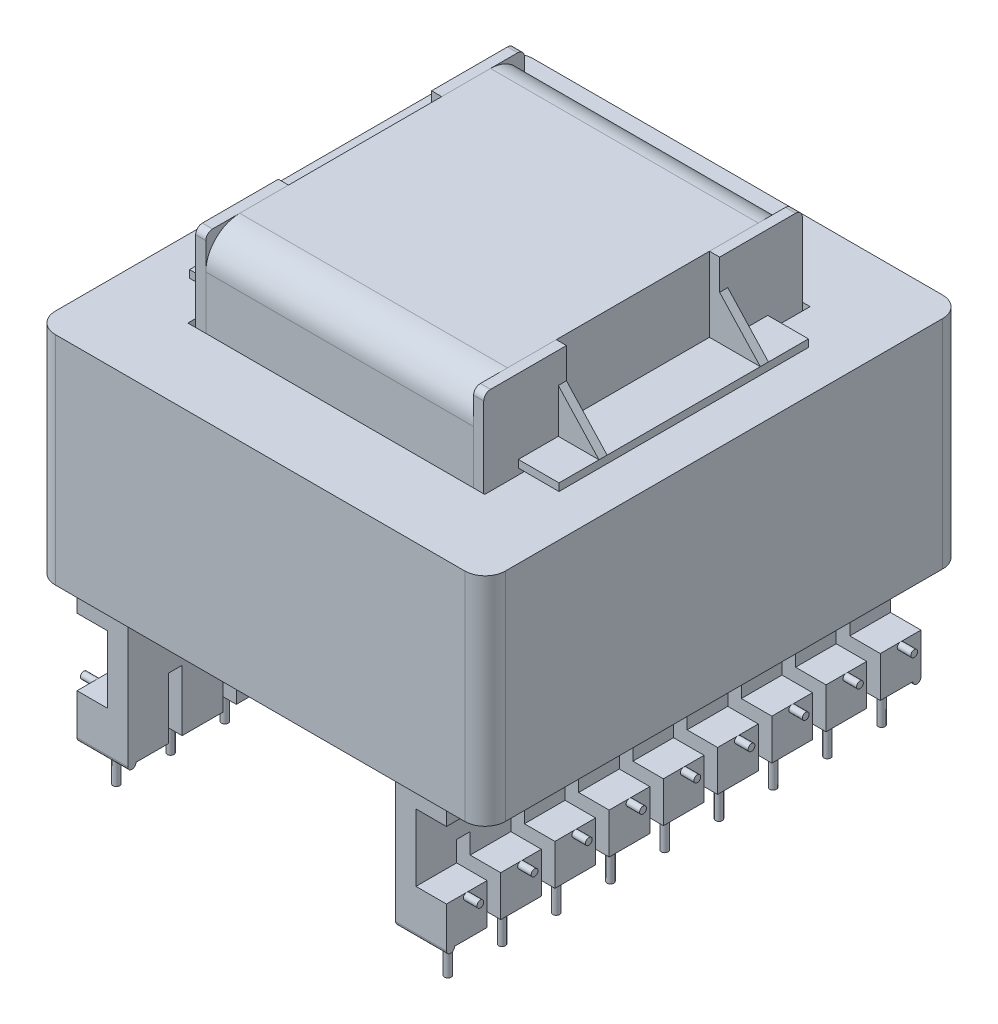
SolidWorks part; units mm, degrees
ref_plane "Спереди" through (0, 0, 0) normal (0, 0, 1) x (1, 0, 0)
ref_plane "Сверху" through (0, 0, 0) normal (0, 1, 0) x (1, 0, 0)
ref_plane "Справа" through (0, 0, 0) normal (1, 0, 0) x (0, 0, -1)
sketch "Эскиз1" plane through (0, 0, 0) normal (1, 0, 0) x (0, 0, -1)
  line L1 (-11.3, 16.25) -> (11.3, 16.25)
  line L2 (-11.3, 16.25) -> (-11.3, -16.25)
  line L3 (-11.3, -16.25) -> (11.3, -16.25)
  line L4 (11.3, 16.25) -> (11.3, -16.25)
  line L5 (-11.3, 16.25) -> (11.3, -16.25) construction
  line L6 (-11.3, -16.25) -> (11.3, 16.25) construction
  line L7 (-12.5, 17.35) -> (12.5, 17.35)
  line L8 (-12.5, 17.35) -> (-12.5, -17.35)
  line L9 (-12.5, -17.35) -> (12.5, -17.35)
  line L10 (12.5, 17.35) -> (12.5, -17.35)
  line L11 (-12.5, 17.35) -> (12.5, -17.35) construction
  line L12 (-12.5, -17.35) -> (12.5, 17.35) construction
  point P0 (0, 0)
  point P6 (0, 0)
  dimension "D1" = 22.6
  dimension "D2" = 32.5
  dimension "D3" = 25
  dimension "D4" = 34.7
extrude "Бобышка-Вытянуть1" add sketch "Эскиз1" along normal blind 19.75
sketch "Эскиз2" plane through (19.75, 0, 0) normal (1, 0, 0) x (0, 0, -1)
  line L0 (-12.5, -17.35) -> (12.5, -17.35) construction
  line L1 (11.3, -17.35) -> (23.5, -17.35)
  line L2 (11.3, -17.35) -> (11.3, 28.35)
  line L3 (11.3, 28.35) -> (22.5, 28.35)
  line L4 (23.5, -17.35) -> (23.5, 27.35)
  line L5 (11.3, 16.25) -> (-11.3, 16.25) construction
  line L6 (11.3, -16.25) -> (11.3, 16.25) construction
  line L7 (0, 0) -> (0, 38.0092) construction
  line L8 (-23.5, -17.35) -> (-23.5, 27.35)
  line L9 (-11.3, 28.35) -> (-22.5, 28.35)
  line L10 (-11.3, -17.35) -> (-11.3, 28.35)
  line L11 (-11.3, -17.35) -> (-23.5, -17.35)
  arc A0 (22.5, 28.35) -> (23.5, 27.35) centre (22.5, 27.35) cw
  arc A1 (-22.5, 28.35) -> (-23.5, 27.35) centre (-22.5, 27.35) ccw
  dimension "D3" = 1
  dimension "D1" = 23.5
  dimension "D2" = 12.1
extrude "Бобышка-Вытянуть2" add sketch "Эскиз2" along normal blind 1.5
sketch "Эскиз3" plane through (19.75, 0, 0) normal (1, 0, 0) x (0, 0, -1)
  line L0 (11.3, 16.25) -> (-11.3, 16.25) construction
  line L1 (18.4, 16.25) -> (-18.4, 16.25)
  line L2 (0, 16.25) -> (0, 17.35)
  line L3 (18.4, 17.35) -> (-18.4, 17.35)
  line L4 (-18.4, 16.25) -> (-18.4, 17.35)
  line L5 (11.3, 17.35) -> (-11.3, 17.35) construction
  line L6 (18.4, 16.25) -> (18.4, 17.35)
  line L7 (-11.3, -17.35) -> (11.3, -17.35) construction
  line L8 (-35, -17.35) -> (35, -17.35)
  line L9 (0, -17.35) -> (0, -16.25)
  line L10 (-35, -16.25) -> (35, -16.25)
  line L11 (35, -17.35) -> (35, -16.25)
  line L12 (-11.3, -16.25) -> (11.3, -16.25) construction
  line L13 (-35, -17.35) -> (-35, -16.25)
  dimension "D1" = 18.4
  dimension "D2" = 35
extrude "Бобышка-Вытянуть3" add sketch "Эскиз3" along normal blind 7.5 contours L1 L4 L3 L6 | L10 L11 L8 L13
sketch "Эскиз4" plane through (0, 17.35, 0) normal (0, 1, 0) x (1, 0, 0)
  line L0 (27.25, 18.4) -> (27.25, -18.4) construction
  line L1 (21.25, -11.3) -> (27.25, -11.3)
  line L2 (21.25, -11.3) -> (21.25, -12.5)
  line L3 (21.25, -12.5) -> (27.25, -12.5)
  line L4 (27.25, -11.3) -> (27.25, -12.5)
  line L5 (19.75, 12.5) -> (0, 12.5) construction
  line L6 (21.25, 11.3) -> (27.25, 11.3)
  line L7 (21.25, 11.3) -> (21.25, 12.5)
  line L8 (21.25, 12.5) -> (27.25, 12.5)
  line L9 (27.25, 11.3) -> (27.25, 12.5)
  line L10 (19.75, -12.5) -> (0, -12.5) construction
  point P16 (0, 0)
  point P17 (0, 0)
  point P18 (0, 0)
extrude "Бобышка-Вытянуть4" add sketch "Эскиз4" along normal blind 6.5 contours L8 L9 L6 L7 | L1 L4 L3 L2
sketch "Эскиз5" plane through (0, 0, -12.5) normal (0, 0, -1) x (-1, 0, 0)
  line L0 (-21.25, 23.85) -> (-27.25, 17.35)
  line L1 (-27.25, 17.35) -> (-27.25, 23.85)
  line L2 (-27.25, 23.85) -> (-21.25, 23.85)
  line L3 (-21.25, 23.85) -> (-21.2719, 23.84)
extrude "Вырез-Вытянуть1" cut sketch "Эскиз5" against normal through all
sketch "Эскиз6" plane through (0, -17.35, 0) normal (0, -1, 0) x (-1, 0, 0)
  line L1 (-27.25, -35) -> (-19.75, -35)
  line L2 (-27.25, -35) -> (-27.25, 35)
  line L3 (-27.25, 35) -> (-19.75, 35)
  line L4 (-19.75, -35) -> (-19.75, 35)
extrude "Бобышка-Вытянуть5" add sketch "Эскиз6" along normal offset from surface (16.8 mm away) 62.5 up to face at (20.5, 28.35, -16.9)
sketch "Эскиз7" plane through (0, 0, -35) normal (0, 0, -1) x (-1, 0, 0)
  line L0 (-27.25, -34.15) -> (-27.25, -16.25) construction
  line L1 (-27.25, -28.15) -> (-22.75, -28.15)
  line L2 (-27.25, -28.15) -> (-27.25, -18.25)
  line L3 (-27.25, -18.25) -> (-22.75, -18.25)
  line L4 (-22.75, -28.15) -> (-22.75, -18.25)
  line L5 (-19.75, -34.15) -> (-19.75, -16.25) construction
  line L6 (-27.25, -16.25) -> (-19.75, -16.25) construction
  line L7 (-19.75, -34.15) -> (-27.25, -34.15) construction
  dimension "D1" = 3
  dimension "D2" = 2
  dimension "D3" = 6
extrude "Вырез-Вытянуть2" cut sketch "Эскиз7" against normal up to next
sketch "Эскиз9" plane through (0, -34.15, 0) normal (0, -1, 0) x (1, 0, 0)
  line L0 (0, 12.5) -> (0, -12.5) construction
  circle A0 centre (24.45, 32) radius 0.5
  circle A1 centre (24.45, 24) radius 0.5
  circle A2 centre (24.45, 16) radius 0.5
  circle A3 centre (24.45, 8) radius 0.5
  circle A4 centre (24.45, 0) radius 0.5
  circle A5 centre (24.45, -8) radius 0.5
  circle A6 centre (24.45, -16) radius 0.5
  circle A7 centre (24.45, -24) radius 0.5
  circle A8 centre (24.45, -32) radius 0.5
  dimension "D3" = 1
  dimension "D1" = 24.45
  dimension "D2" = 32
  dimension "D4" = 9
extrude "Бобышка-Вытянуть6" add sketch "Эскиз9" along normal blind 6
sketch "Эскиз10" plane through (27.25, 0, 0) normal (1, 0, 0) x (0, 0, -1)
  line L0 (35, -34.15) -> (-35, -34.15) construction
  line L1 (-29, -34.15) -> (-27, -34.15)
  line L2 (-29, -34.15) -> (-29, -25.15)
  line L3 (-29, -25.15) -> (-27, -25.15)
  line L4 (-27, -34.15) -> (-27, -25.15)
  line L5 (-35, -28.15) -> (35, -28.15) construction
  line L6 (-35, -34.15) -> (-35, -28.15) construction
  line L7 (-21, -34.15) -> (-19, -34.15)
  line L8 (-21, -34.15) -> (-21, -25.15)
  line L9 (-21, -25.15) -> (-19, -25.15)
  line L10 (-19, -34.15) -> (-19, -25.15)
  line L11 (-13, -34.15) -> (-11, -34.15)
  line L12 (-13, -34.15) -> (-13, -25.15)
  line L13 (-13, -25.15) -> (-11, -25.15)
  line L14 (-11, -34.15) -> (-11, -25.15)
  line L15 (-5, -34.15) -> (-3, -34.15)
  line L16 (-5, -34.15) -> (-5, -25.15)
  line L17 (-5, -25.15) -> (-3, -25.15)
  line L18 (-3, -34.15) -> (-3, -25.15)
  line L19 (3, -34.15) -> (5, -34.15)
  line L20 (3, -34.15) -> (3, -25.15)
  line L21 (3, -25.15) -> (5, -25.15)
  line L22 (5, -34.15) -> (5, -25.15)
  line L23 (11, -34.15) -> (13, -34.15)
  line L24 (11, -34.15) -> (11, -25.15)
  line L25 (11, -25.15) -> (13, -25.15)
  line L26 (13, -34.15) -> (13, -25.15)
  line L27 (19, -34.15) -> (21, -34.15)
  line L28 (19, -34.15) -> (19, -25.15)
  line L29 (19, -25.15) -> (21, -25.15)
  line L30 (21, -34.15) -> (21, -25.15)
  line L31 (27, -34.15) -> (29, -34.15)
  line L32 (27, -34.15) -> (27, -25.15)
  line L33 (27, -25.15) -> (29, -25.15)
  line L34 (29, -34.15) -> (29, -25.15)
  dimension "D1" = 3
  dimension "D2" = 6
  dimension "D3" = 2
  dimension "D4" = 8
extrude "Вырез-Вытянуть3" cut sketch "Эскиз10" against normal up to next
sketch "Эскиз11" plane through (27.25, 0, 0) normal (1, 0, 0) x (0, 0, -1)
  line L0 (-35, -28.15) -> (-29, -28.15) construction
  circle A0 centre (-32, -28.65) radius 0.5
  circle A1 centre (-24, -28.65) radius 0.5
  circle A2 centre (-16, -28.65) radius 0.5
  circle A3 centre (-8, -28.65) radius 0.5
  circle A4 centre (0, -28.65) radius 0.5
  circle A5 centre (8, -28.65) radius 0.5
  circle A6 centre (16, -28.65) radius 0.5
  circle A7 centre (24, -28.65) radius 0.5
  circle A8 centre (32, -28.65) radius 0.5
  point P2 (-32, -28.15)
  point P9 (-24, -28.15)
  point P13 (-16, -28.15)
  point P16 (-8, -28.15)
  point P19 (0, -28.15)
  point P22 (8, -28.15)
  point P25 (16, -28.15)
  point P28 (24, -28.15)
  point P31 (32, -28.15)
  dimension "D1" = 1
  dimension "D2" = 9
extrude "Бобышка-Вытянуть7" add sketch "Эскиз11" along normal blind 2
sketch "Эскиз13" plane through (27.25, 0, 0) normal (1, 0, 0) x (0, 0, -1)
  line L0 (-29, -34.15) -> (-35, -34.15) construction
  line L1 (-35, -34.15) -> (-33.8, -34.15)
  line L2 (0, -49.1553) -> (0, -4.971) construction
  line L3 (35, -34.15) -> (33.8, -34.15)
  arc A0 (-35, -34.15) -> (-33.8, -34.15) centre (-34.4, -34.15) ccw
  arc A1 (35, -34.15) -> (33.8, -34.15) centre (34.4, -34.15) cw
  dimension "D1" = 0.6
  dimension "D2" = 1.2
extrude "Бобышка-Вытянуть9" add sketch "Эскиз13" against normal up to surface (7.5 mm away) contours A1 L3 | A0 L1 up to face at (19.75, -17.5777, 0)
mirror "Зеркальное отражение1" of "Бобышка-Вытянуть9", "Бобышка-Вытянуть7", "Вырез-Вытянуть3", "Бобышка-Вытянуть6", "Вырез-Вытянуть2", "Бобышка-Вытянуть5", "Вырез-Вытянуть1", "Бобышка-Вытянуть3", "Бобышка-Вытянуть2", "Бобышка-Вытянуть1", "Бобышка-Вытянуть4"
sketch "Эскиз12" plane through (0, 0, -18.4) normal (0, 0, -1) x (-1, 0, 0)
  line L0 (21.25, 17.35) -> (27.25, 17.35)
  line L1 (27.25, 17.35) -> (21.25, 23.85)
  line L2 (21.25, 23.85) -> (21.25, 17.35)
  point P5 (0, 0)
  point P6 (21.25, 24.797)
  point P7 (21.25, 23.85)
extrude "Бобышка-Вытянуть8" add sketch "Эскиз12" against normal blind 1.5
sketch "Эскиз14" plane through (0, 0, 0) normal (1, 0, 0) x (0, 0, -1)
  line L0 (0, 0) -> (0, -16.25) construction
  line L1 (35.25, 16) -> (24, 16)
  line L2 (35.25, 16) -> (35.25, -16)
  line L3 (35.25, -16) -> (24, -16)
  line L4 (24, 16) -> (24, -16)
  line L5 (35.25, 16) -> (24, -16) construction
  line L6 (35.25, -16) -> (24, 16) construction
  line L7 (-35, -16.25) -> (35, -16.25) construction
  line L8 (-35.25, -16) -> (-24, 16) construction
  line L9 (-35.25, 16) -> (-24, -16) construction
  line L10 (-24, 16) -> (-24, -16)
  line L11 (-35.25, -16) -> (-24, -16)
  line L12 (-35.25, 16) -> (-35.25, -16)
  line L13 (-35.25, 16) -> (-24, 16)
  point P0 (29.625, 0)
  point P15 (-29.625, 0)
  dimension "D1" = 35.25
  dimension "D2" = 32
  dimension "D3" = 11.25
extrude "Бобышка-Вытянуть10" add sketch "Эскиз14" along normal blind 33.2 separate body
sketch "Эскиз15" plane through (33.2, 0, 0) normal (1, 0, 0) x (0, 0, -1)
  line L1 (24, -16) -> (-24, -16)
  line L2 (24, -16) -> (24, 16)
  line L3 (24, 16) -> (-24, 16)
  line L4 (-24, -16) -> (-24, 16)
  line L5 (24, -16) -> (-24, 16) construction
  line L6 (24, 16) -> (-24, -16) construction
  point P0 (0, 0)
extrude "Бобышка-Вытянуть11" add sketch "Эскиз15" against normal blind 11.3
sketch "Эскиз16" plane through (21.9, 0, 0) normal (-1, 0, 0) x (0, 0, 1)
  line L0 (24, -16) -> (-24, -16) construction
  line L1 (-11, 16) -> (11, 16)
  line L2 (-11, 16) -> (-11, -16)
  line L3 (-11, -16) -> (11, -16)
  line L4 (11, 16) -> (11, -16)
  line L5 (-11, 16) -> (11, -16) construction
  line L6 (-11, -16) -> (11, 16) construction
  point P0 (0, 0)
  dimension "D1" = 22
extrude "Бобышка-Вытянуть12" add sketch "Эскиз16" along normal blind 15.9
fillet "Скругление1" radius 3 2 edges at (33.2, 0, 35.25) (33.2, 0, -35.25)
mirror "Зеркальное отражение2" of "Бобышка-Вытянуть10", "Бобышка-Вытянуть11", "Бобышка-Вытянуть12", "Скругление1"
sketch "Эскиз17" plane through (-19.75, 0, 0) normal (1, 0, 0) x (0, 0, -1)
  line L0 (22.5, 28.35) -> (11.3, 28.35) construction
  line L1 (-12.5, -17.35) -> (12.5, -17.35)
  line L2 (-12.5, -17.35) -> (-12.5, 17.35)
  line L3 (-12.5, 17.35) -> (12.5, 17.35)
  line L4 (12.5, -17.35) -> (12.5, 17.35)
  line L5 (-12.5, -17.35) -> (12.5, 17.35) construction
  line L6 (-12.5, 17.35) -> (12.5, -17.35) construction
  line L7 (-18.5, -28.35) -> (18.5, -28.35)
  line L8 (-23.5, -23.35) -> (-23.5, 23.35)
  line L9 (-18.5, 28.35) -> (18.5, 28.35)
  line L10 (23.5, -23.35) -> (23.5, 23.35)
  line L11 (-23.5, -28.35) -> (23.5, 28.35) construction
  line L12 (-23.5, 28.35) -> (23.5, -28.35) construction
  line L13 (23.5, -16.25) -> (23.5, 27.35) construction
  arc A0 (-23.5, 23.35) -> (-18.5, 28.35) centre (-18.5, 23.35) cw
  arc A1 (-18.5, -28.35) -> (-23.5, -23.35) centre (-18.5, -23.35) cw
  arc A2 (18.5, -28.35) -> (23.5, -23.35) centre (18.5, -23.35) ccw
  arc A3 (18.5, 28.35) -> (23.5, 23.35) centre (18.5, 23.35) cw
  point P0 (0, 0)
  point P6 (0, 0)
  point P8 (0, 0)
  point P13 (24.1233, 28.8908)
  point P18 (0, 0)
  dimension "D1" = 5
extrude "Бобышка-Вытянуть14" add sketch "Эскиз17" along normal up to surface (39.5 mm away) separate body up to face at (19.75, -18.2382, 0)
